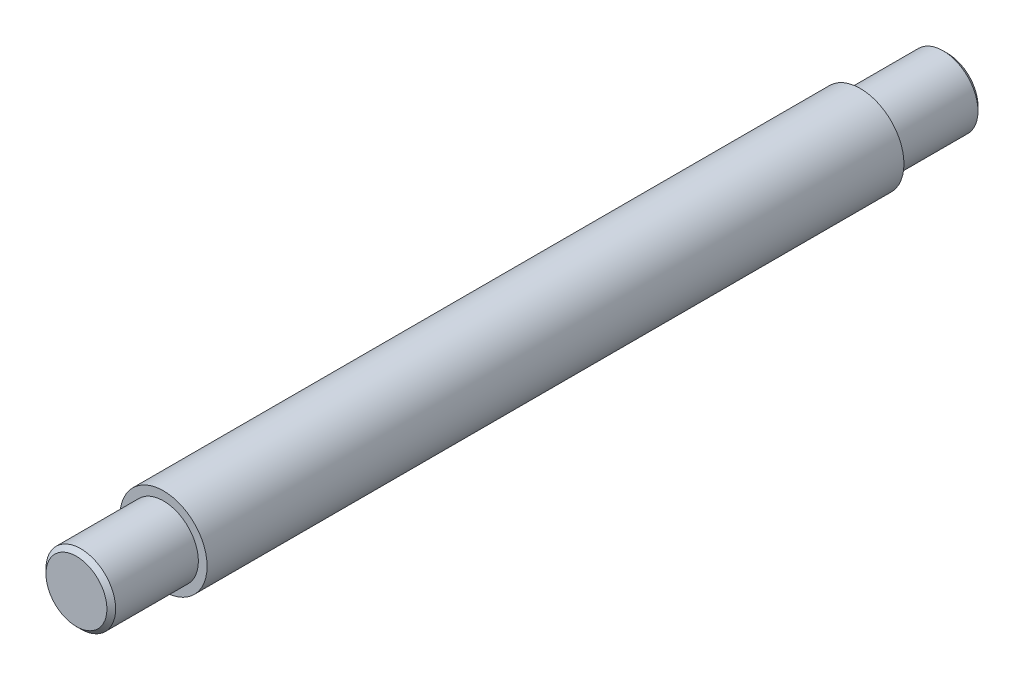
SolidWorks part; units mm, degrees
material "1.7225 (42CrMo4)"
ref_plane "Front Plane" through (0, 0, 0) normal (0, 0, 1) x (1, 0, 0)
ref_plane "Top Plane" through (0, 0, 0) normal (0, 1, 0) x (1, 0, 0)
ref_plane "Right Plane" through (0, 0, 0) normal (1, 0, 0) x (0, 0, -1)
sketch "Esquisse1" plane through (0, 0, 0) normal (0, 0, 1) x (1, 0, 0)
  circle A0 centre (0, 0) radius 4
  dimension "D1" = 8
extrude "Boss.-Extru.1" add sketch "Esquisse1" along normal blind 10
cosmetic thread "Représentation de filetage1" parameters "D2"=6.619
sketch "Esquisse2" plane through (0, 0, 10) normal (0, 0, 1) x (1, 0, 0)
  circle A0 centre (0, 0) radius 5
  dimension "D1" = 10
extrude "Boss.-Extru.2" add sketch "Esquisse2" along normal blind 80
sketch "Esquisse3" plane through (0, 0, 90) normal (0, 0, 1) x (1, 0, 0)
  circle A0 centre (0, 0) radius 4
  dimension "D1" = 8
extrude "Boss.-Extru.3" add sketch "Esquisse3" along normal blind 10
cosmetic thread "Représentation de filetage2" parameters "D2"=6.619
chamfer "Chanfrein1" distance 0.5 angle 45 2 edges at (4, 0, 0) (4, 0, 100)
